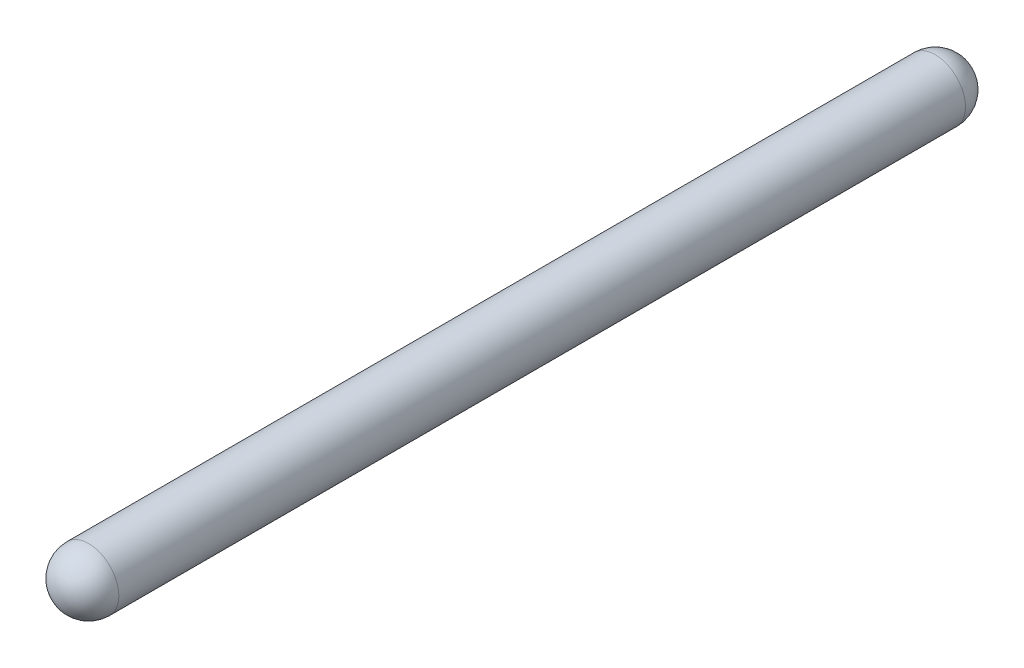
SolidWorks part; units mm, degrees
material "AISI 4130 Steel, normalized at 870C"
ref_plane "Front Plane" through (0, 0, 0) normal (0, 0, 1) x (1, 0, 0)
ref_plane "Top Plane" through (0, 0, 0) normal (0, 1, 0) x (1, 0, 0)
ref_plane "Right Plane" through (0, 0, 0) normal (1, 0, 0) x (0, 0, -1)
sketch "Sketch2" plane through (0, 0, 0) normal (0, 0, 1) x (1, 0, 0)
  circle A0 centre (0, 0) radius 1
extrude "Boss-Extrude4" add sketch "Sketch2" along normal blind 30
fillet "Fillet2" radius 1 2 edges at (1, 0, 0) (1, 0, 30)
